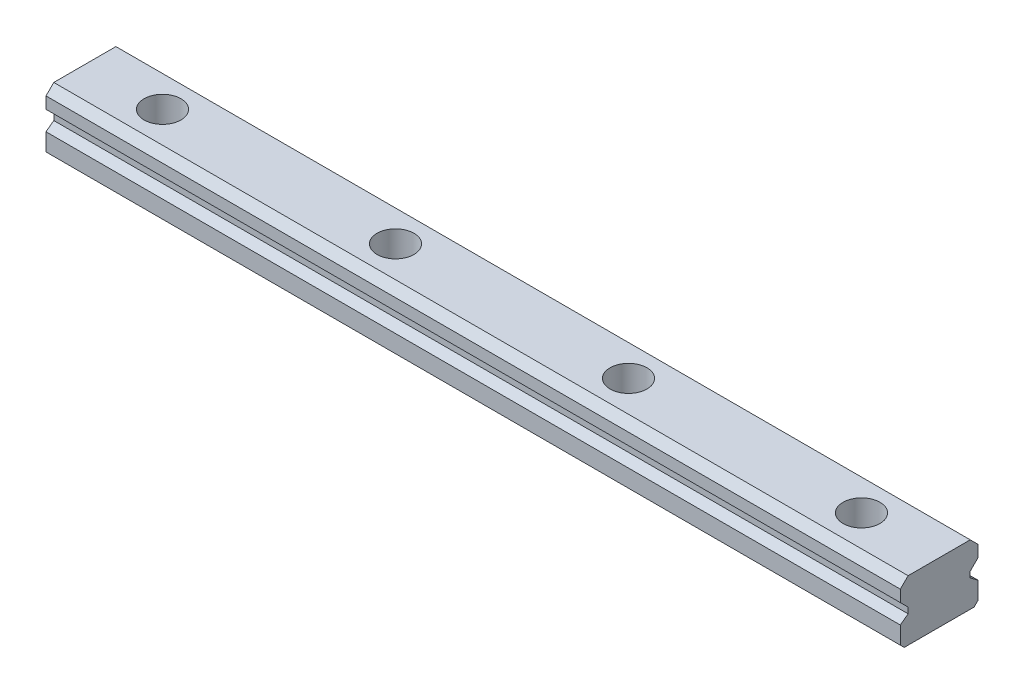
SolidWorks part; units mm, degrees
material "201 Annealed Stainless Steel (SS)"
ref_plane "Front Plane" through (0, 0, 0) normal (0, 0, 1) x (1, 0, 0)
ref_plane "Top Plane" through (0, 0, 0) normal (0, 1, 0) x (1, 0, 0)
ref_plane "Right Plane" through (0, 0, 0) normal (1, 0, 0) x (0, 0, -1)
sketch "Sketch1" plane through (0, 0, 0) normal (1, 0, 0) x (0, 0, -1)
  line L0 (0, 39.5089) -> (0, 0) construction
  line L1 (9, 0) -> (-9, 0)
  line L2 (-9, 0) -> (-10, 1)
  line L3 (-10, 1) -> (-10, 5.5)
  line L4 (-10, 5.5) -> (-8, 7)
  line L5 (-8, 7) -> (-8, 8.5)
  line L6 (-8, 8.5) -> (-10, 10.5)
  line L7 (-10, 10.5) -> (-10, 13.5)
  line L8 (-10, 13.5) -> (-8, 15.5)
  line L9 (-8, 15.5) -> (8, 15.5)
  line L10 (-18.0832, 7.75) -> (13.0406, 7.75) construction
  line L11 (-4.25, 15.5) -> (-4.25, 7) construction
  line L12 (-4.25, 7) -> (-3, 7) construction
  line L13 (-3, 7) -> (-3, 0) construction
  line L14 (4.25, 15.5) -> (4.25, 7) construction
  line L15 (4.25, 7) -> (3, 7) construction
  line L16 (3, 7) -> (3, 0) construction
  line L17 (9, 0) -> (10, 1)
  line L18 (10, 1) -> (10, 5.5)
  line L19 (10, 5.5) -> (8, 7)
  line L20 (8, 7) -> (8, 8.5)
  line L21 (8, 8.5) -> (10, 10.5)
  line L22 (10, 13.5) -> (8, 15.5)
  line L23 (10, 10.5) -> (10, 13.5)
  point P14 (-8, 7.75)
  point P32 (0, 15.5)
  dimension "D1" = 10
  dimension "D2" = 1
  dimension "D3" = 1
  dimension "D4" = 5.5
  dimension "D5" = 7.75
  dimension "D6" = 15.5
  dimension "D7" = 4.25
  dimension "D8" = 3
  dimension "D9" = 8.5
  dimension "D10" = 7
  dimension "D11" = 2
  dimension "D12" = 2
  dimension "D13" = 2
  dimension "D14" = 2
extrude "Boss-Extrude1" add sketch "Sketch1" along normal blind 220
sketch "Sketch2" plane through (0, 15.5, 0) normal (0, 1, 0) x (1, 0, 0)
  line L0 (0, 0) -> (220, 0) construction
  line L1 (0, 8) -> (0, -8) construction
  line L2 (220, 8) -> (220, -8) construction
  circle A0 centre (20, 0) radius 4.75
  dimension "D1" = 9.5
  dimension "D2" = 20
extrude "Cut-Extrude1" cut sketch "Sketch2" against normal blind 8.5
sketch "Sketch3" plane through (0, 7, 0) normal (0, 1, 0) x (1, 0, 0)
  circle A0 centre (20, 0) radius 3
  dimension "D1" = 6
extrude "Cut-Extrude2" cut sketch "Sketch3" against normal through all
pattern_linear "LPattern1" count 4 spacing 60 along (1, 0, 0) of "Cut-Extrude2", "Cut-Extrude1"
